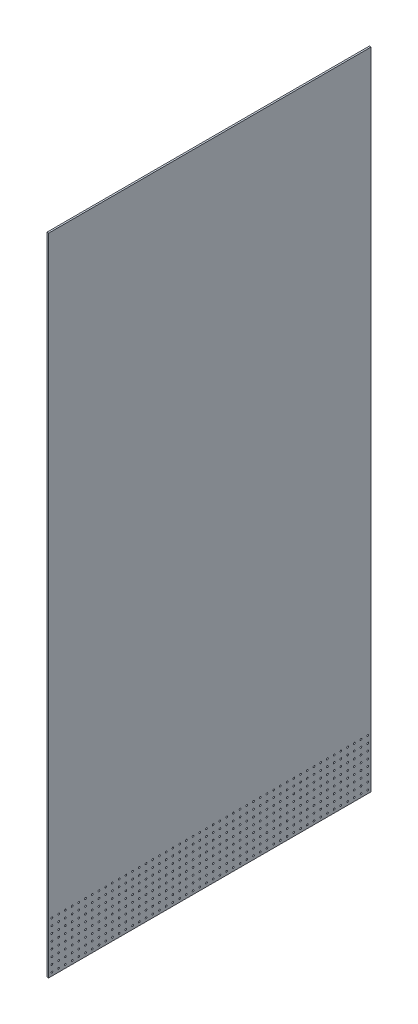
SolidWorks part; units mm, degrees
ref_plane "Front Plane" through (0, 0, 0) normal (1, 0, 0) x (0, 1, 0)
ref_plane "Top Plane" through (0, 0, 0) normal (0, 0, 1) x (0, 1, 0)
ref_plane "Right Plane" through (0, 0, 0) normal (0, 1, 0) x (-1, 0, 0)
sketch "Initial hole" plane through (0, 0, 0) normal (1, 0, 0) x (0, 1, 0)
  line L0 (-1206.5, 596.9) -> (-1181.1, 596.9) construction
  line L1 (-1219.2, -609.6) -> (1219.2, -609.6)
  line L2 (-1219.2, -609.6) -> (-1219.2, 609.6)
  line L3 (-1219.2, 609.6) -> (1219.2, 609.6)
  line L4 (1219.2, -609.6) -> (1219.2, 609.6)
  line L5 (-1219.2, -609.6) -> (1219.2, 609.6) construction
  line L6 (-1219.2, 609.6) -> (1219.2, -609.6) construction
  line L7 (-1206.5, 596.9) -> (-1206.5, 571.5) construction
  circle A0 centre (-1206.5, 596.9) radius 3.175
  circle A1 centre (-1181.1, 596.9) radius 3.175
  circle A2 centre (-1155.7, 596.9) radius 3.175
  circle A3 centre (-1130.3, 596.9) radius 3.175
  circle A4 centre (-1104.9, 596.9) radius 3.175
  circle A5 centre (-1079.5, 596.9) radius 3.175
  circle A6 centre (-1054.1, 596.9) radius 3.175
  circle A7 centre (-1028.7, 596.9) radius 3.175
  circle A8 centre (-1181.1, 571.5) radius 3.175
  circle A9 centre (-1155.7, 571.5) radius 3.175
  circle A10 centre (-1130.3, 571.5) radius 3.175
  circle A11 centre (-1104.9, 571.5) radius 3.175
  circle A12 centre (-1079.5, 571.5) radius 3.175
  circle A13 centre (-1054.1, 571.5) radius 3.175
  circle A14 centre (-1028.7, 571.5) radius 3.175
  circle A15 centre (-1181.1, 546.1) radius 3.175
  circle A16 centre (-1155.7, 546.1) radius 3.175
  circle A17 centre (-1130.3, 546.1) radius 3.175
  circle A18 centre (-1104.9, 546.1) radius 3.175
  circle A19 centre (-1079.5, 546.1) radius 3.175
  circle A20 centre (-1054.1, 546.1) radius 3.175
  circle A21 centre (-1028.7, 546.1) radius 3.175
  circle A22 centre (-1181.1, 520.7) radius 3.175
  circle A23 centre (-1155.7, 520.7) radius 3.175
  circle A24 centre (-1130.3, 520.7) radius 3.175
  circle A25 centre (-1104.9, 520.7) radius 3.175
  circle A26 centre (-1079.5, 520.7) radius 3.175
  circle A27 centre (-1054.1, 520.7) radius 3.175
  circle A28 centre (-1028.7, 520.7) radius 3.175
  circle A29 centre (-1181.1, 495.3) radius 3.175
  circle A30 centre (-1155.7, 495.3) radius 3.175
  circle A31 centre (-1130.3, 495.3) radius 3.175
  circle A32 centre (-1104.9, 495.3) radius 3.175
  circle A33 centre (-1079.5, 495.3) radius 3.175
  circle A34 centre (-1054.1, 495.3) radius 3.175
  circle A35 centre (-1028.7, 495.3) radius 3.175
  circle A36 centre (-1181.1, 469.9) radius 3.175
  circle A37 centre (-1155.7, 469.9) radius 3.175
  circle A38 centre (-1130.3, 469.9) radius 3.175
  circle A39 centre (-1104.9, 469.9) radius 3.175
  circle A40 centre (-1079.5, 469.9) radius 3.175
  circle A41 centre (-1054.1, 469.9) radius 3.175
  circle A42 centre (-1028.7, 469.9) radius 3.175
  circle A43 centre (-1181.1, 444.5) radius 3.175
  circle A44 centre (-1155.7, 444.5) radius 3.175
  circle A45 centre (-1130.3, 444.5) radius 3.175
  circle A46 centre (-1104.9, 444.5) radius 3.175
  circle A47 centre (-1079.5, 444.5) radius 3.175
  circle A48 centre (-1054.1, 444.5) radius 3.175
  circle A49 centre (-1028.7, 444.5) radius 3.175
  circle A50 centre (-1181.1, 419.1) radius 3.175
  circle A51 centre (-1155.7, 419.1) radius 3.175
  circle A52 centre (-1130.3, 419.1) radius 3.175
  circle A53 centre (-1104.9, 419.1) radius 3.175
  circle A54 centre (-1079.5, 419.1) radius 3.175
  circle A55 centre (-1054.1, 419.1) radius 3.175
  circle A56 centre (-1028.7, 419.1) radius 3.175
  circle A57 centre (-1206.5, 571.5) radius 3.175
  circle A58 centre (-1206.5, 546.1) radius 3.175
  circle A59 centre (-1206.5, 520.7) radius 3.175
  circle A60 centre (-1206.5, 495.3) radius 3.175
  circle A61 centre (-1206.5, 469.9) radius 3.175
  circle A62 centre (-1206.5, 444.5) radius 3.175
  circle A63 centre (-1206.5, 419.1) radius 3.175
  circle A64 centre (-1206.5, 393.7) radius 3.175
  circle A65 centre (-1181.1, 393.7) radius 3.175
  circle A66 centre (-1155.7, 393.7) radius 3.175
  circle A67 centre (-1130.3, 393.7) radius 3.175
  circle A68 centre (-1104.9, 393.7) radius 3.175
  circle A69 centre (-1079.5, 393.7) radius 3.175
  circle A70 centre (-1054.1, 393.7) radius 3.175
  circle A71 centre (-1028.7, 393.7) radius 3.175
  circle A72 centre (-1206.5, 368.3) radius 3.175
  circle A73 centre (-1181.1, 368.3) radius 3.175
  circle A74 centre (-1155.7, 368.3) radius 3.175
  circle A75 centre (-1130.3, 368.3) radius 3.175
  circle A76 centre (-1104.9, 368.3) radius 3.175
  circle A77 centre (-1079.5, 368.3) radius 3.175
  circle A78 centre (-1054.1, 368.3) radius 3.175
  circle A79 centre (-1028.7, 368.3) radius 3.175
  circle A80 centre (-1206.5, 342.9) radius 3.175
  circle A81 centre (-1181.1, 342.9) radius 3.175
  circle A82 centre (-1155.7, 342.9) radius 3.175
  circle A83 centre (-1130.3, 342.9) radius 3.175
  circle A84 centre (-1104.9, 342.9) radius 3.175
  circle A85 centre (-1079.5, 342.9) radius 3.175
  circle A86 centre (-1054.1, 342.9) radius 3.175
  circle A87 centre (-1028.7, 342.9) radius 3.175
  circle A88 centre (-1206.5, 317.5) radius 3.175
  circle A89 centre (-1181.1, 317.5) radius 3.175
  circle A90 centre (-1155.7, 317.5) radius 3.175
  circle A91 centre (-1130.3, 317.5) radius 3.175
  circle A92 centre (-1104.9, 317.5) radius 3.175
  circle A93 centre (-1079.5, 317.5) radius 3.175
  circle A94 centre (-1054.1, 317.5) radius 3.175
  circle A95 centre (-1028.7, 317.5) radius 3.175
  circle A96 centre (-1206.5, 292.1) radius 3.175
  circle A97 centre (-1181.1, 292.1) radius 3.175
  circle A98 centre (-1155.7, 292.1) radius 3.175
  circle A99 centre (-1130.3, 292.1) radius 3.175
  circle A100 centre (-1104.9, 292.1) radius 3.175
  circle A101 centre (-1079.5, 292.1) radius 3.175
  circle A102 centre (-1054.1, 292.1) radius 3.175
  circle A103 centre (-1028.7, 292.1) radius 3.175
  circle A104 centre (-1206.5, 266.7) radius 3.175
  circle A105 centre (-1181.1, 266.7) radius 3.175
  circle A106 centre (-1155.7, 266.7) radius 3.175
  circle A107 centre (-1130.3, 266.7) radius 3.175
  circle A108 centre (-1104.9, 266.7) radius 3.175
  circle A109 centre (-1079.5, 266.7) radius 3.175
  circle A110 centre (-1054.1, 266.7) radius 3.175
  circle A111 centre (-1028.7, 266.7) radius 3.175
  circle A112 centre (-1206.5, 241.3) radius 3.175
  circle A113 centre (-1181.1, 241.3) radius 3.175
  circle A114 centre (-1155.7, 241.3) radius 3.175
  circle A115 centre (-1130.3, 241.3) radius 3.175
  circle A116 centre (-1104.9, 241.3) radius 3.175
  circle A117 centre (-1079.5, 241.3) radius 3.175
  circle A118 centre (-1054.1, 241.3) radius 3.175
  circle A119 centre (-1028.7, 241.3) radius 3.175
  circle A120 centre (-1206.5, 215.9) radius 3.175
  circle A121 centre (-1181.1, 215.9) radius 3.175
  circle A122 centre (-1155.7, 215.9) radius 3.175
  circle A123 centre (-1130.3, 215.9) radius 3.175
  circle A124 centre (-1104.9, 215.9) radius 3.175
  circle A125 centre (-1079.5, 215.9) radius 3.175
  circle A126 centre (-1054.1, 215.9) radius 3.175
  circle A127 centre (-1028.7, 215.9) radius 3.175
  circle A128 centre (-1206.5, 190.5) radius 3.175
  circle A129 centre (-1181.1, 190.5) radius 3.175
  circle A130 centre (-1155.7, 190.5) radius 3.175
  circle A131 centre (-1130.3, 190.5) radius 3.175
  circle A132 centre (-1104.9, 190.5) radius 3.175
  circle A133 centre (-1079.5, 190.5) radius 3.175
  circle A134 centre (-1054.1, 190.5) radius 3.175
  circle A135 centre (-1028.7, 190.5) radius 3.175
  circle A136 centre (-1206.5, 165.1) radius 3.175
  circle A137 centre (-1181.1, 165.1) radius 3.175
  circle A138 centre (-1155.7, 165.1) radius 3.175
  circle A139 centre (-1130.3, 165.1) radius 3.175
  circle A140 centre (-1104.9, 165.1) radius 3.175
  circle A141 centre (-1079.5, 165.1) radius 3.175
  circle A142 centre (-1054.1, 165.1) radius 3.175
  circle A143 centre (-1028.7, 165.1) radius 3.175
  circle A144 centre (-1206.5, 139.7) radius 3.175
  circle A145 centre (-1181.1, 139.7) radius 3.175
  circle A146 centre (-1155.7, 139.7) radius 3.175
  circle A147 centre (-1130.3, 139.7) radius 3.175
  circle A148 centre (-1104.9, 139.7) radius 3.175
  circle A149 centre (-1079.5, 139.7) radius 3.175
  circle A150 centre (-1054.1, 139.7) radius 3.175
  circle A151 centre (-1028.7, 139.7) radius 3.175
  circle A152 centre (-1206.5, 114.3) radius 3.175
  circle A153 centre (-1181.1, 114.3) radius 3.175
  circle A154 centre (-1155.7, 114.3) radius 3.175
  circle A155 centre (-1130.3, 114.3) radius 3.175
  circle A156 centre (-1104.9, 114.3) radius 3.175
  circle A157 centre (-1079.5, 114.3) radius 3.175
  circle A158 centre (-1054.1, 114.3) radius 3.175
  circle A159 centre (-1028.7, 114.3) radius 3.175
  circle A160 centre (-1206.5, 88.9) radius 3.175
  circle A161 centre (-1181.1, 88.9) radius 3.175
  circle A162 centre (-1155.7, 88.9) radius 3.175
  circle A163 centre (-1130.3, 88.9) radius 3.175
  circle A164 centre (-1104.9, 88.9) radius 3.175
  circle A165 centre (-1079.5, 88.9) radius 3.175
  circle A166 centre (-1054.1, 88.9) radius 3.175
  circle A167 centre (-1028.7, 88.9) radius 3.175
  circle A168 centre (-1206.5, 63.5) radius 3.175
  circle A169 centre (-1181.1, 63.5) radius 3.175
  circle A170 centre (-1155.7, 63.5) radius 3.175
  circle A171 centre (-1130.3, 63.5) radius 3.175
  circle A172 centre (-1104.9, 63.5) radius 3.175
  circle A173 centre (-1079.5, 63.5) radius 3.175
  circle A174 centre (-1054.1, 63.5) radius 3.175
  circle A175 centre (-1028.7, 63.5) radius 3.175
  circle A176 centre (-1206.5, 38.1) radius 3.175
  circle A177 centre (-1181.1, 38.1) radius 3.175
  circle A178 centre (-1155.7, 38.1) radius 3.175
  circle A179 centre (-1130.3, 38.1) radius 3.175
  circle A180 centre (-1104.9, 38.1) radius 3.175
  circle A181 centre (-1079.5, 38.1) radius 3.175
  circle A182 centre (-1054.1, 38.1) radius 3.175
  circle A183 centre (-1028.7, 38.1) radius 3.175
  circle A184 centre (-1206.5, 12.7) radius 3.175
  circle A185 centre (-1181.1, 12.7) radius 3.175
  circle A186 centre (-1155.7, 12.7) radius 3.175
  circle A187 centre (-1130.3, 12.7) radius 3.175
  circle A188 centre (-1104.9, 12.7) radius 3.175
  circle A189 centre (-1079.5, 12.7) radius 3.175
  circle A190 centre (-1054.1, 12.7) radius 3.175
  circle A191 centre (-1028.7, 12.7) radius 3.175
  circle A192 centre (-1206.5, -12.7) radius 3.175
  circle A193 centre (-1181.1, -12.7) radius 3.175
  circle A194 centre (-1155.7, -12.7) radius 3.175
  circle A195 centre (-1130.3, -12.7) radius 3.175
  circle A196 centre (-1104.9, -12.7) radius 3.175
  circle A197 centre (-1079.5, -12.7) radius 3.175
  circle A198 centre (-1054.1, -12.7) radius 3.175
  circle A199 centre (-1028.7, -12.7) radius 3.175
  circle A200 centre (-1206.5, -38.1) radius 3.175
  circle A201 centre (-1181.1, -38.1) radius 3.175
  circle A202 centre (-1155.7, -38.1) radius 3.175
  circle A203 centre (-1130.3, -38.1) radius 3.175
  circle A204 centre (-1104.9, -38.1) radius 3.175
  circle A205 centre (-1079.5, -38.1) radius 3.175
  circle A206 centre (-1054.1, -38.1) radius 3.175
  circle A207 centre (-1028.7, -38.1) radius 3.175
  circle A208 centre (-1206.5, -63.5) radius 3.175
  circle A209 centre (-1181.1, -63.5) radius 3.175
  circle A210 centre (-1155.7, -63.5) radius 3.175
  circle A211 centre (-1130.3, -63.5) radius 3.175
  circle A212 centre (-1104.9, -63.5) radius 3.175
  circle A213 centre (-1079.5, -63.5) radius 3.175
  circle A214 centre (-1054.1, -63.5) radius 3.175
  circle A215 centre (-1028.7, -63.5) radius 3.175
  circle A216 centre (-1206.5, -88.9) radius 3.175
  circle A217 centre (-1181.1, -88.9) radius 3.175
  circle A218 centre (-1155.7, -88.9) radius 3.175
  circle A219 centre (-1130.3, -88.9) radius 3.175
  circle A220 centre (-1104.9, -88.9) radius 3.175
  circle A221 centre (-1079.5, -88.9) radius 3.175
  circle A222 centre (-1054.1, -88.9) radius 3.175
  circle A223 centre (-1028.7, -88.9) radius 3.175
  circle A224 centre (-1206.5, -114.3) radius 3.175
  circle A225 centre (-1181.1, -114.3) radius 3.175
  circle A226 centre (-1155.7, -114.3) radius 3.175
  circle A227 centre (-1130.3, -114.3) radius 3.175
  circle A228 centre (-1104.9, -114.3) radius 3.175
  circle A229 centre (-1079.5, -114.3) radius 3.175
  circle A230 centre (-1054.1, -114.3) radius 3.175
  circle A231 centre (-1028.7, -114.3) radius 3.175
  circle A232 centre (-1206.5, -139.7) radius 3.175
  circle A233 centre (-1181.1, -139.7) radius 3.175
  circle A234 centre (-1155.7, -139.7) radius 3.175
  circle A235 centre (-1130.3, -139.7) radius 3.175
  circle A236 centre (-1104.9, -139.7) radius 3.175
  circle A237 centre (-1079.5, -139.7) radius 3.175
  circle A238 centre (-1054.1, -139.7) radius 3.175
  circle A239 centre (-1028.7, -139.7) radius 3.175
  circle A240 centre (-1206.5, -165.1) radius 3.175
  circle A241 centre (-1181.1, -165.1) radius 3.175
  circle A242 centre (-1155.7, -165.1) radius 3.175
  circle A243 centre (-1130.3, -165.1) radius 3.175
  circle A244 centre (-1104.9, -165.1) radius 3.175
  circle A245 centre (-1079.5, -165.1) radius 3.175
  circle A246 centre (-1054.1, -165.1) radius 3.175
  circle A247 centre (-1028.7, -165.1) radius 3.175
  circle A248 centre (-1206.5, -190.5) radius 3.175
  circle A249 centre (-1181.1, -190.5) radius 3.175
  circle A250 centre (-1155.7, -190.5) radius 3.175
  circle A251 centre (-1130.3, -190.5) radius 3.175
  circle A252 centre (-1104.9, -190.5) radius 3.175
  circle A253 centre (-1079.5, -190.5) radius 3.175
  circle A254 centre (-1054.1, -190.5) radius 3.175
  circle A255 centre (-1028.7, -190.5) radius 3.175
  circle A256 centre (-1206.5, -215.9) radius 3.175
  circle A257 centre (-1181.1, -215.9) radius 3.175
  circle A258 centre (-1155.7, -215.9) radius 3.175
  circle A259 centre (-1130.3, -215.9) radius 3.175
  circle A260 centre (-1104.9, -215.9) radius 3.175
  circle A261 centre (-1079.5, -215.9) radius 3.175
  circle A262 centre (-1054.1, -215.9) radius 3.175
  circle A263 centre (-1028.7, -215.9) radius 3.175
  circle A264 centre (-1206.5, -241.3) radius 3.175
  circle A265 centre (-1181.1, -241.3) radius 3.175
  circle A266 centre (-1155.7, -241.3) radius 3.175
  circle A267 centre (-1130.3, -241.3) radius 3.175
  circle A268 centre (-1104.9, -241.3) radius 3.175
  circle A269 centre (-1079.5, -241.3) radius 3.175
  circle A270 centre (-1054.1, -241.3) radius 3.175
  circle A271 centre (-1028.7, -241.3) radius 3.175
  circle A272 centre (-1206.5, -266.7) radius 3.175
  circle A273 centre (-1181.1, -266.7) radius 3.175
  circle A274 centre (-1155.7, -266.7) radius 3.175
  circle A275 centre (-1130.3, -266.7) radius 3.175
  circle A276 centre (-1104.9, -266.7) radius 3.175
  circle A277 centre (-1079.5, -266.7) radius 3.175
  circle A278 centre (-1054.1, -266.7) radius 3.175
  circle A279 centre (-1028.7, -266.7) radius 3.175
  circle A280 centre (-1206.5, -292.1) radius 3.175
  circle A281 centre (-1181.1, -292.1) radius 3.175
  circle A282 centre (-1155.7, -292.1) radius 3.175
  circle A283 centre (-1130.3, -292.1) radius 3.175
  circle A284 centre (-1104.9, -292.1) radius 3.175
  circle A285 centre (-1079.5, -292.1) radius 3.175
  circle A286 centre (-1054.1, -292.1) radius 3.175
  circle A287 centre (-1028.7, -292.1) radius 3.175
  circle A288 centre (-1206.5, -317.5) radius 3.175
  circle A289 centre (-1181.1, -317.5) radius 3.175
  circle A290 centre (-1155.7, -317.5) radius 3.175
  circle A291 centre (-1130.3, -317.5) radius 3.175
  circle A292 centre (-1104.9, -317.5) radius 3.175
  circle A293 centre (-1079.5, -317.5) radius 3.175
  circle A294 centre (-1054.1, -317.5) radius 3.175
  circle A295 centre (-1028.7, -317.5) radius 3.175
  circle A296 centre (-1206.5, -342.9) radius 3.175
  circle A297 centre (-1181.1, -342.9) radius 3.175
  circle A298 centre (-1155.7, -342.9) radius 3.175
  circle A299 centre (-1130.3, -342.9) radius 3.175
  circle A300 centre (-1104.9, -342.9) radius 3.175
  circle A301 centre (-1079.5, -342.9) radius 3.175
  circle A302 centre (-1054.1, -342.9) radius 3.175
  circle A303 centre (-1028.7, -342.9) radius 3.175
  circle A304 centre (-1206.5, -368.3) radius 3.175
  circle A305 centre (-1181.1, -368.3) radius 3.175
  circle A306 centre (-1155.7, -368.3) radius 3.175
  circle A307 centre (-1130.3, -368.3) radius 3.175
  circle A308 centre (-1104.9, -368.3) radius 3.175
  circle A309 centre (-1079.5, -368.3) radius 3.175
  circle A310 centre (-1054.1, -368.3) radius 3.175
  circle A311 centre (-1028.7, -368.3) radius 3.175
  circle A312 centre (-1206.5, -393.7) radius 3.175
  circle A313 centre (-1181.1, -393.7) radius 3.175
  circle A314 centre (-1155.7, -393.7) radius 3.175
  circle A315 centre (-1130.3, -393.7) radius 3.175
  circle A316 centre (-1104.9, -393.7) radius 3.175
  circle A317 centre (-1079.5, -393.7) radius 3.175
  circle A318 centre (-1054.1, -393.7) radius 3.175
  circle A319 centre (-1028.7, -393.7) radius 3.175
  circle A320 centre (-1206.5, -419.1) radius 3.175
  circle A321 centre (-1181.1, -419.1) radius 3.175
  circle A322 centre (-1155.7, -419.1) radius 3.175
  circle A323 centre (-1130.3, -419.1) radius 3.175
  circle A324 centre (-1104.9, -419.1) radius 3.175
  circle A325 centre (-1079.5, -419.1) radius 3.175
  circle A326 centre (-1054.1, -419.1) radius 3.175
  circle A327 centre (-1028.7, -419.1) radius 3.175
  circle A328 centre (-1206.5, -444.5) radius 3.175
  circle A329 centre (-1181.1, -444.5) radius 3.175
  circle A330 centre (-1155.7, -444.5) radius 3.175
  circle A331 centre (-1130.3, -444.5) radius 3.175
  circle A332 centre (-1104.9, -444.5) radius 3.175
  circle A333 centre (-1079.5, -444.5) radius 3.175
  circle A334 centre (-1054.1, -444.5) radius 3.175
  circle A335 centre (-1028.7, -444.5) radius 3.175
  circle A336 centre (-1206.5, -469.9) radius 3.175
  circle A337 centre (-1181.1, -469.9) radius 3.175
  circle A338 centre (-1155.7, -469.9) radius 3.175
  circle A339 centre (-1130.3, -469.9) radius 3.175
  circle A340 centre (-1104.9, -469.9) radius 3.175
  circle A341 centre (-1079.5, -469.9) radius 3.175
  circle A342 centre (-1054.1, -469.9) radius 3.175
  circle A343 centre (-1028.7, -469.9) radius 3.175
  circle A344 centre (-1206.5, -495.3) radius 3.175
  circle A345 centre (-1181.1, -495.3) radius 3.175
  circle A346 centre (-1155.7, -495.3) radius 3.175
  circle A347 centre (-1130.3, -495.3) radius 3.175
  circle A348 centre (-1104.9, -495.3) radius 3.175
  circle A349 centre (-1079.5, -495.3) radius 3.175
  circle A350 centre (-1054.1, -495.3) radius 3.175
  circle A351 centre (-1028.7, -495.3) radius 3.175
  circle A352 centre (-1206.5, -520.7) radius 3.175
  circle A353 centre (-1181.1, -520.7) radius 3.175
  circle A354 centre (-1155.7, -520.7) radius 3.175
  circle A355 centre (-1130.3, -520.7) radius 3.175
  circle A356 centre (-1104.9, -520.7) radius 3.175
  circle A357 centre (-1079.5, -520.7) radius 3.175
  circle A358 centre (-1054.1, -520.7) radius 3.175
  circle A359 centre (-1028.7, -520.7) radius 3.175
  circle A360 centre (-1206.5, -546.1) radius 3.175
  circle A361 centre (-1181.1, -546.1) radius 3.175
  circle A362 centre (-1155.7, -546.1) radius 3.175
  circle A363 centre (-1130.3, -546.1) radius 3.175
  circle A364 centre (-1104.9, -546.1) radius 3.175
  circle A365 centre (-1079.5, -546.1) radius 3.175
  circle A366 centre (-1054.1, -546.1) radius 3.175
  circle A367 centre (-1028.7, -546.1) radius 3.175
  circle A368 centre (-1206.5, -571.5) radius 3.175
  circle A369 centre (-1181.1, -571.5) radius 3.175
  circle A370 centre (-1155.7, -571.5) radius 3.175
  circle A371 centre (-1130.3, -571.5) radius 3.175
  circle A372 centre (-1104.9, -571.5) radius 3.175
  circle A373 centre (-1079.5, -571.5) radius 3.175
  circle A374 centre (-1054.1, -571.5) radius 3.175
  circle A375 centre (-1028.7, -571.5) radius 3.175
  circle A376 centre (-1206.5, -596.9) radius 3.175
  circle A377 centre (-1181.1, -596.9) radius 3.175
  circle A378 centre (-1155.7, -596.9) radius 3.175
  circle A379 centre (-1130.3, -596.9) radius 3.175
  circle A380 centre (-1104.9, -596.9) radius 3.175
  circle A381 centre (-1079.5, -596.9) radius 3.175
  circle A382 centre (-1054.1, -596.9) radius 3.175
  circle A383 centre (-1028.7, -596.9) radius 3.175
  point P0 (0, 0)
  dimension "D4" = 6.35
  dimension "D1" = 2438.4
  dimension "D2" = 1219.2
  dimension "D3" = 12.7
  dimension "D5" = 12.7
  dimension "D8" = 90
  dimension "D9" = 25.4
  dimension "D10" = 25.4
  dimension "D6" = 8
  dimension "D7" = 48
extrude "Boss-Extrude1" add sketch "Initial hole" along normal blind 6.35
